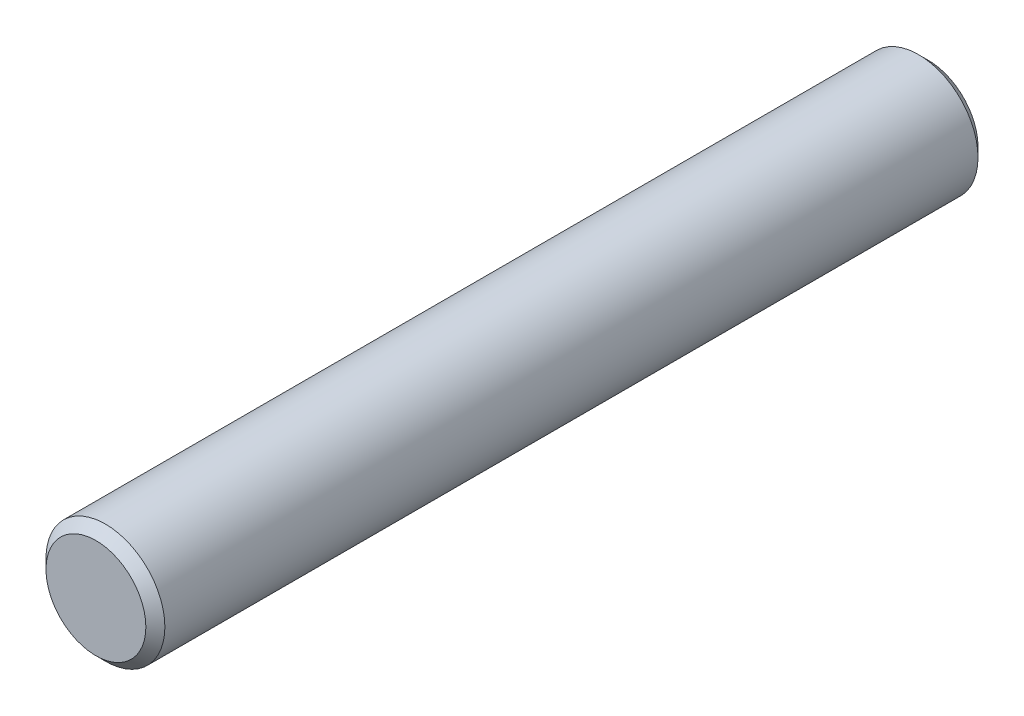
SolidWorks part; units mm, degrees
material "Plain Carbon Steel"
ref_plane "Front Plane" through (0, 0, 0) normal (0, 0, 1) x (1, 0, 0)
ref_plane "Top Plane" through (0, 0, 0) normal (0, 1, 0) x (1, 0, 0)
ref_plane "Right Plane" through (0, 0, 0) normal (1, 0, 0) x (0, 0, -1)
sketch "Sketch1" plane through (0, 0, 0) normal (0, 0, 1) x (1, 0, 0)
  circle A0 centre (0, 0) radius 1.5875
  dimension "D1" = 3.175
extrude "Boss-Extrude1" add sketch "Sketch1" along normal blind 22.225
chamfer "Chamfer1" distance 0.254 angle 45 2 edges at (1.5875, 0, 0) (1.5875, 0, 22.225)
